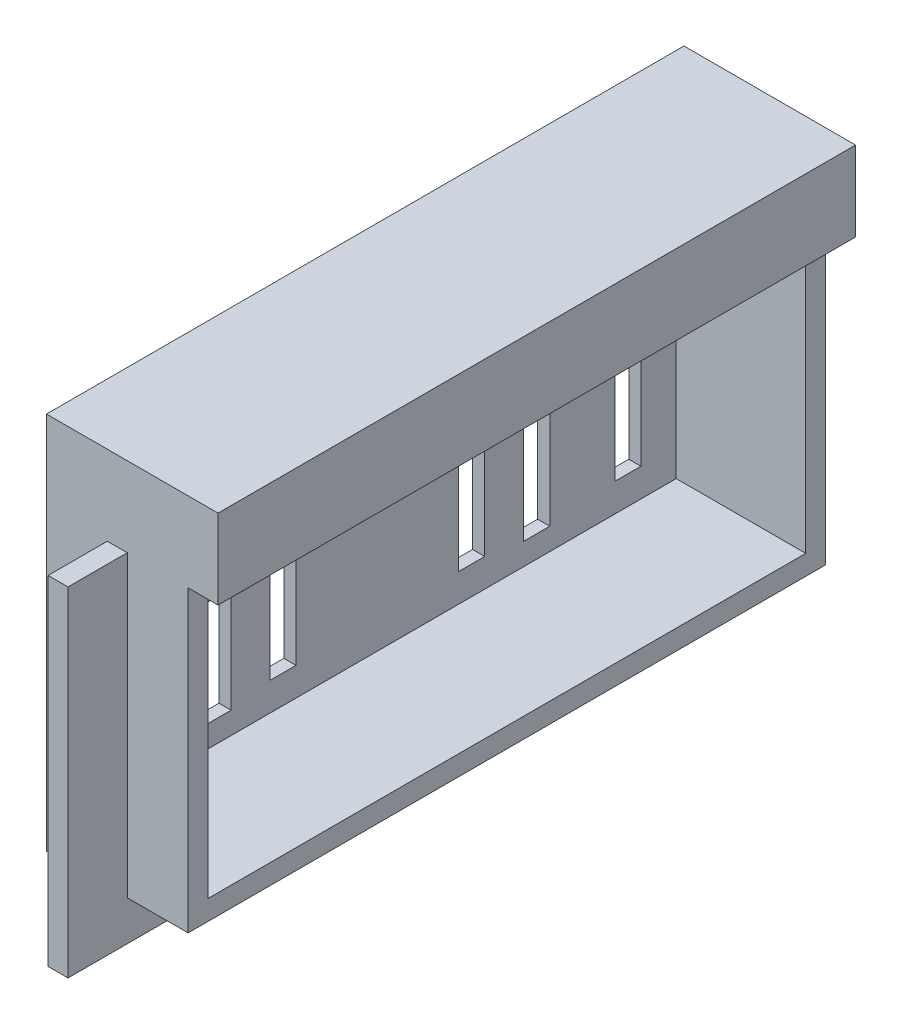
SolidWorks part; units mm, degrees
ref_plane "前视基准面" through (0, 0, 0) normal (0, 0, 1) x (1, 0, 0)
ref_plane "上视基准面" through (0, 0, 0) normal (0, 1, 0) x (1, 0, 0)
ref_plane "右视基准面" through (0, 0, 0) normal (1, 0, 0) x (0, 0, -1)
other "Configuration Table"
sketch "草图1" plane through (0, 0, 0) normal (0, 1, 0) x (1, 0, 0)
  line L0 (-2, 0) -> (0, 0)
  line L1 (0, 0) -> (0, 5.9476)
  line L2 (0, 5.9476) -> (6.111, 5.9476)
  line L3 (6.111, 5.9476) -> (6.111, 69.9476)
  line L5 (-8.111, 5.9476) -> (-8.111, 69.9476)
  line L6 (-2, 5.9476) -> (-8.111, 5.9476)
  line L7 (-2, 0) -> (-2, 5.9476)
  line L8 (-2, 75.8953) -> (-2, 69.9476)
  line L9 (-2, 69.9476) -> (-8.111, 69.9476)
  line L10 (0, 69.9476) -> (6.111, 69.9476)
  line L11 (0, 75.8953) -> (0, 69.9476)
  line L12 (-2, 75.8953) -> (0, 75.8953)
  point P14 (6.111, 37.9476)
  dimension "D2" = 5.9476
  dimension "D3" = 6.111
  dimension "D4" = 32
extrude "凸台-拉伸1" add sketch "草图1" along normal blind 38 contours L12 L8 L9 L5 L6 L7 L0 L1 L2 L3 L10 L11
sketch "草图2" plane through (6.111, 0, 0) normal (1, 0, 0) x (0, 0, -1)
  line L1 (7.9476, 2) -> (67.9476, 2)
  line L2 (7.9476, 2) -> (7.9476, 36)
  line L3 (7.9476, 36) -> (67.9476, 36)
  line L4 (67.9476, 2) -> (67.9476, 36)
  line L5 (7.9476, 2) -> (67.9476, 36) construction
  line L6 (7.9476, 36) -> (67.9476, 2) construction
  point P0 (37.9476, 19)
  point P7 (0, 0)
extrude "切除-拉伸1" cut sketch "草图2" against normal blind 13
sketch "草图3" plane through (-8.111, 0, 0) normal (-1, 0, 0) x (0, 0, 1)
  line L0 (-69.9476, 19) -> (-5.9476, 19)
  line L3 (-37.9476, 38) -> (-37.9476, 36.6686)
  line L6 (-69.9476, 38) -> (-58.2469, 31.0527)
  line L8 (-5.9476, 38) -> (-17.6484, 31.0527)
  line L9 (-69.9476, 19) -> (-58.2469, 25.9473)
  line L10 (-5.9476, 19) -> (-17.6484, 25.9473)
  line L11 (-37.9476, 0) -> (-29.779, 4.8501)
  line L12 (-37.9476, 0) -> (-52.6394, 8.7232)
  line L13 (-48.9476, 28.5) -> (-46.1054, 28.5)
  line L14 (-52.6394, 9.5) -> (-48.7219, 9.5)
  line L15 (-55.2559, 4.2066) -> (-52.6394, 4.2066)
  line L16 (-55.2559, 4.2066) -> (-55.2559, 14.7934)
  line L17 (-55.2559, 14.7934) -> (-52.6394, 14.7934)
  line L18 (-52.6394, 4.2066) -> (-52.6394, 14.7934)
  line L19 (-63.9358, 15.4305) -> (-69.9476, 19)
  line L21 (-46.1054, 28.5) -> (-46.1054, 4.8437)
  line L22 (-29.779, 28.5) -> (-29.779, 4.8501)
  line L23 (-48.7219, 4.8437) -> (-46.1054, 4.8437)
  line L24 (-46.1054, 4.8437) -> (-46.1054, 15.4305)
  line L25 (-48.7219, 4.8437) -> (-48.7219, 15.4305)
  line L26 (-48.7219, 15.4305) -> (-46.1054, 15.4305)
  line L27 (-29.779, 4.8501) -> (-27.1625, 4.8501)
  line L28 (-27.1625, 4.8501) -> (-27.1625, 15.4369)
  line L29 (-29.779, 4.8501) -> (-29.779, 15.4369)
  line L30 (-29.779, 15.4369) -> (-27.1625, 15.4369)
  line L31 (-61.7899, 4.8437) -> (-61.7899, 15.4305)
  line L32 (-61.7899, 15.4305) -> (-64.4064, 15.4305)
  line L33 (-64.4064, 4.8437) -> (-64.4064, 15.4305)
  line L34 (-61.7899, 4.8437) -> (-64.4064, 4.8437)
  line L35 (-23.2559, 14.7934) -> (-20.6394, 14.7934)
  line L36 (-23.2559, 4.2066) -> (-23.2559, 14.7934)
  line L37 (-23.2559, 4.2066) -> (-20.6394, 4.2066)
  line L38 (-20.6394, 4.2066) -> (-20.6394, 14.7934)
  line L39 (-11.4998, 4.8501) -> (-11.4998, 15.4369)
  line L40 (-11.4998, 15.4369) -> (-14.1163, 15.4369)
  line L41 (-14.1163, 4.8501) -> (-14.1163, 15.4369)
  line L42 (-11.4998, 4.8501) -> (-14.1163, 4.8501)
  line L43 (-49.6484, 25.9473) -> (-29.779, 14.1499)
  line L44 (-49.6484, 31.0527) -> (-37.9476, 38)
  line L45 (-37.9476, 20.3314) -> (-37.9476, 0)
  line L46 (-29.779, 28.5) -> (-26.9476, 28.5)
  line L47 (-26.2469, 31.0527) -> (-37.9476, 38)
  line L48 (-26.2469, 25.9473) -> (-46.1054, 14.1563)
  line L49 (-20.6394, 8.7232) -> (-5.9476, 0)
  line L50 (-20.6394, 10.2768) -> (-14.1163, 14.1499)
  line L51 (-11.9487, 15.4369) -> (-5.9476, 19)
  line L52 (-27.1625, 9.5) -> (-23.2559, 9.5)
  line L53 (-27.1625, 12.5963) -> (-23.2559, 10.2768)
  line L54 (-27.1625, 6.4037) -> (-23.2559, 8.7232)
  line L55 (-48.7219, 12.6028) -> (-52.6394, 10.2768)
  line L56 (-46.1054, 9.5) -> (-29.779, 9.5)
  line L57 (-55.2559, 10.2768) -> (-61.7899, 14.1563)
  line L58 (-55.2559, 8.7232) -> (-69.9476, 0)
  circle A0 centre (-53.9476, 28.5) radius 5
  circle A1 centre (-21.9476, 28.5) radius 5
  circle A2 centre (-37.9476, 28.5) radius 8.1686
  point P27 (-53.9476, 9.5)
  point P50 (-21.9476, 9.5)
  point P82 (0, 0)
extrude "切除-拉伸4" cut sketch "草图3" against normal blind 31 contours A2 L13 L21 | A0 | A1 | L42 L39 L40 L41 | L37 L38 L35 L36 | L30 L22 L29 L27 L28 | L26 L25 L12 L21 L24 | L15 L18 L17 L16 | L34 L31 L32 L33 | L25 L23 L12
sketch "草图4" plane through (0, 0, 0) normal (0, -1, 0) x (1, 0, 0)
  line L1 (-2, 0) -> (0, 0)
  line L2 (-2, 0) -> (-2, -75.8953)
  line L3 (-2, -75.8953) -> (0, -75.8953)
  line L4 (0, 0) -> (0, -75.8953)
extrude "凸台-拉伸3" add sketch "草图4" along normal blind 4
sketch "草图5" plane through (-2, 0, 0) normal (-1, 0, 0) x (0, 0, 1)
  line L0 (-69.9476, 38) -> (-69.9476, 0) construction
  line L1 (-75.8953, 38) -> (-69.9476, 38)
  line L2 (-75.8953, 38) -> (-75.8953, 30)
  line L3 (-75.8953, 30) -> (-69.9476, 30)
  line L4 (-69.9476, 38) -> (-69.9476, 30)
  line L5 (-5.9476, 38) -> (-5.9476, 0) construction
  line L6 (0, 38) -> (-5.9476, 38)
  line L7 (0, 38) -> (0, 30)
  line L8 (0, 30) -> (-5.9476, 30)
  line L9 (-5.9476, 38) -> (-5.9476, 30)
  dimension "D1" = 8
  dimension "D2" = 8
extrude "切除-拉伸5" cut sketch "草图5" against normal blind 4
sketch "草图6" plane through (6.111, 0, 0) normal (1, 0, 0) x (0, 0, -1)
  line L1 (5.9476, 38) -> (69.9476, 38)
  line L2 (5.9476, 38) -> (5.9476, 30)
  line L3 (5.9476, 30) -> (69.9476, 30)
  line L4 (69.9476, 38) -> (69.9476, 30)
extrude "凸台-拉伸4" add sketch "草图6" along normal blind 3
